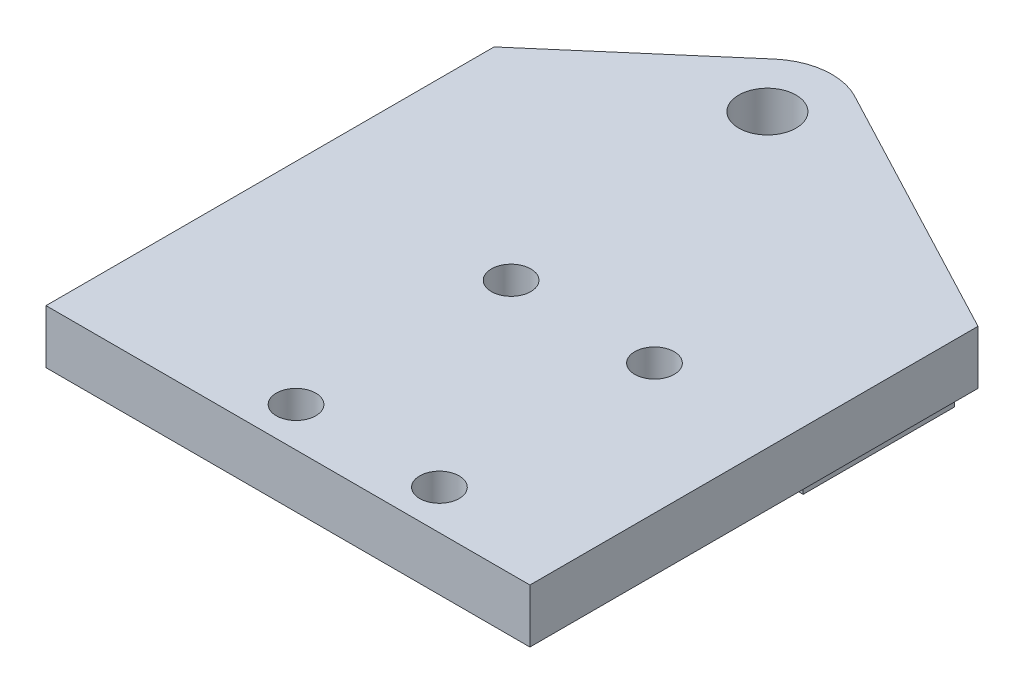
SolidWorks part; units mm, degrees
ref_plane "前视基准面" through (0, 0, 0) normal (0, 0, 1) x (1, 0, 0)
ref_plane "上视基准面" through (0, 0, 0) normal (0, 1, 0) x (1, 0, 0)
ref_plane "右视基准面" through (0, 0, 0) normal (1, 0, 0) x (0, 0, -1)
sketch "草图2" plane through (0, 0, 0) normal (0, 1, 0) x (1, 0, 0)
  line L0 (11.25, 26.9) -> (11.25, -12.1287) construction
  line L1 (-4.5, 0) -> (22.5, 0)
  line L2 (-4.5, 0) -> (-4.5, 25)
  line L4 (22.5, 0) -> (22.5, 25)
  line L5 (3.75, 8.2) -> (23.25, 8.2) construction
  line L6 (-4.5, 25) -> (3.9021, 32.229)
  line L7 (22.5, 25) -> (7.9293, 32.6843)
  circle A0 centre (7.25, 14.2) radius 1.1
  circle A1 centre (15.25, 14.2) radius 1.1
  circle A2 centre (15.25, 2.2) radius 1.1
  circle A3 centre (7.25, 2.2) radius 1.1
  circle A4 centre (6.25, 29.5) radius 1.6
  arc A5 (7.9293, 32.6843) -> (3.9021, 32.229) centre (6.25, 29.5) ccw
  dimension "D3" = 2.2
  dimension "D4" = 8
  dimension "D5" = 12
  dimension "D7" = 3.2
  dimension "D8" = 2
  dimension "D9" = 27
  dimension "D10" = 5
  dimension "D6" = 2.2
  dimension "D1" = 29.5
  dimension "D2" = 25
  dimension "D11" = 11.25
extrude "凸台-拉伸1" add sketch "草图2" along normal blind 3
sketch "草图3" plane through (0, 0, 0) normal (0, -1, 0) x (1, 0, 0)
  line L2 (22.5, -25) -> (7.9293, -32.6843) construction
  line L3 (19.7441, -26.4534) -> (7.9293, -32.6843)
  line L4 (3.9021, -32.229) -> (-4.5, -25) construction
  line L5 (3.9021, -32.229) -> (1.7441, -30.3723)
  line L8 (6.25, -18) -> (6.25, -40.2215) construction
  line L9 (1.7441, -30.3723) -> (1.7441, -18)
  line L10 (1.7441, -18) -> (19.7441, -18)
  line L11 (19.7441, -18) -> (19.7441, -26.4534)
  line L12 (-4.5, 0) -> (22.5, 0) construction
  circle A0 centre (6.25, -29.5) radius 1.6
  arc A2 (3.9021, -32.229) -> (7.9293, -32.6843) centre (6.25, -29.5) ccw construction
  arc A3 (3.9021, -32.229) -> (7.9293, -32.6843) centre (6.25, -29.5) ccw
  circle A4 centre (6.25, -29.5) radius 1.6 construction
  dimension "D1" = 18
  dimension "D2" = 18
extrude "凸台-拉伸2" add sketch "草图3" along normal blind 3
